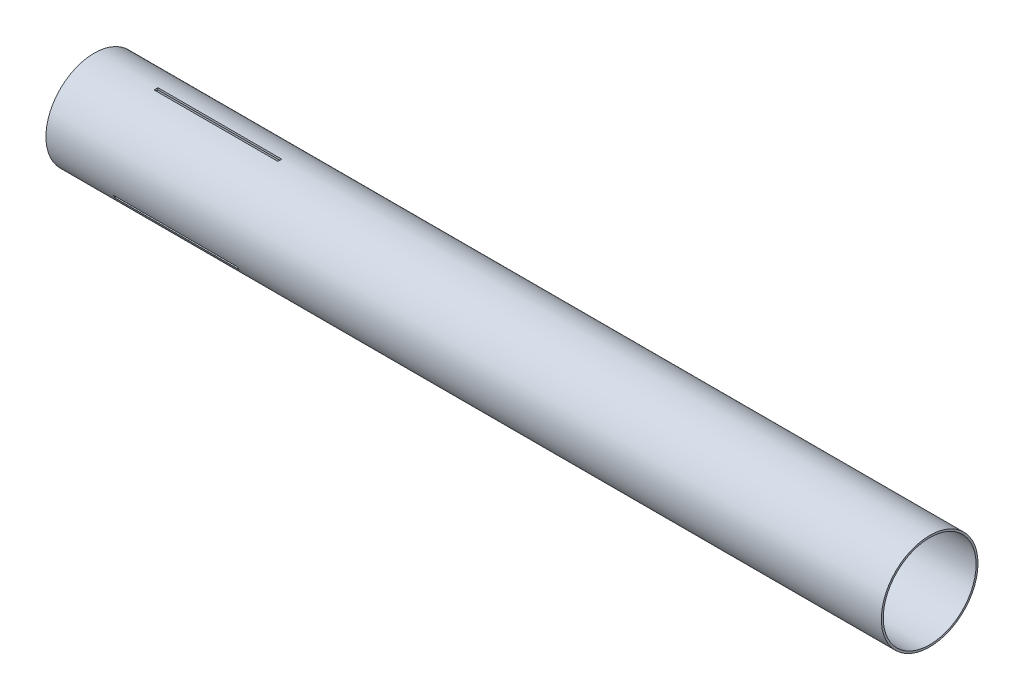
SolidWorks part; units mm, degrees
ref_plane "Front Plane" through (0, 0, 0) normal (0, 0, 1) x (1, 0, 0)
ref_plane "Top Plane" through (0, 0, 0) normal (0, 1, 0) x (1, 0, 0)
ref_plane "Right Plane" through (0, 0, 0) normal (1, 0, 0) x (0, 0, -1)
sketch "Sketch1" plane through (0, 0, 0) normal (1, 0, 0) x (0, 0, -1)
  circle A0 centre (0, 0) radius 39.6748
  circle A2 centre (0, 0) radius 38.1
  dimension "D1" = 79.3496
  dimension "D2" = 76.2
extrude "Boss-Extrude1" add sketch "Sketch1" along normal blind 685.8
ref_plane "Plane1" through (50.8, 0, 0) normal (-1, 0, 0) x (0, 0, 1)
sketch "Sketch2" plane through (50.8, 0, 0) normal (-1, 0, 0) x (0, 0, 1)
  line L0 (-1.5875, 39.643) -> (-1.5875, 38.0669)
  line L1 (1.5875, 39.643) -> (1.5875, 38.0669)
  line L2 (35.1256, -18.4467) -> (33.7607, -17.6586)
  line L3 (33.5381, -21.1963) -> (32.1732, -20.4083)
  line L4 (-33.5381, -21.1963) -> (-32.1732, -20.4083)
  line L5 (-35.1256, -18.4467) -> (-33.7607, -17.6586)
  arc A0 (-35.1256, -18.4467) -> (-33.5381, -21.1963) centre (0, 0) ccw
  arc A1 (-33.7607, -17.6586) -> (-32.1732, -20.4083) centre (0, 0) ccw
  arc A2 (1.5875, 38.0669) -> (-1.5875, 38.0669) centre (0, 0) ccw
  arc A3 (1.5875, 39.643) -> (-1.5875, 39.643) centre (0, 0) ccw
  arc A4 (32.1732, -20.4083) -> (33.7607, -17.6586) centre (0, 0) ccw
  arc A5 (33.5381, -21.1963) -> (35.1256, -18.4467) centre (0, 0) ccw
  point P18 (0, 0)
  dimension "D1" = 79.3496
  dimension "D2" = 76.2
  dimension "D3" = 1.5875
  dimension "D4" = 1.5875
  dimension "D5" = 3
extrude "Cut-Extrude2" cut sketch "Sketch2" against normal blind 101.6
